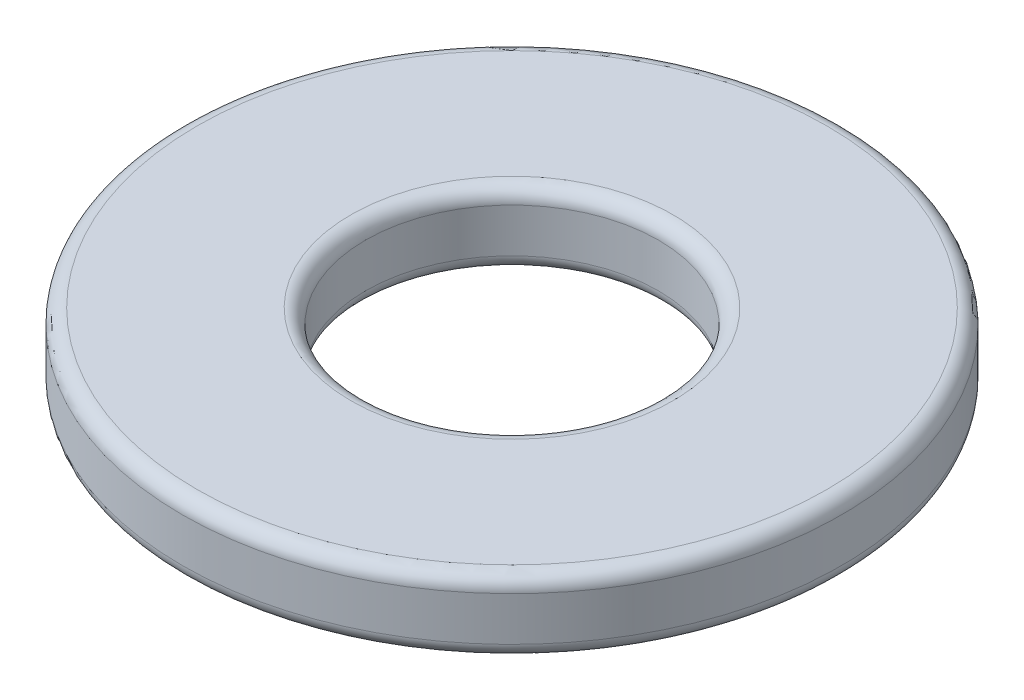
SolidWorks part; units mm, degrees
ref_plane "Front Plane" through (0, 0, 0) normal (0, 0, 1) x (1, 0, 0)
ref_plane "Top Plane" through (0, 0, 0) normal (0, 1, 0) x (1, 0, 0)
ref_plane "Right Plane" through (0, 0, 0) normal (1, 0, 0) x (0, 0, -1)
sketch "Sketch1" plane through (0, 0, 0) normal (0, 1, 0) x (1, 0, 0)
  circle A0 centre (0, 0) radius 2
  circle A1 centre (0, 0) radius 4.5
  dimension "D1" = 4
  dimension "D2" = 9
extrude "Boss-Extrude1" add sketch "Sketch1" along normal blind 1
fillet "Fillet1" radius 0.2 4 edges at (0, 0, 4.5) (0, 1, 4.5) (0, 0, 2) (0, 1, 2)
